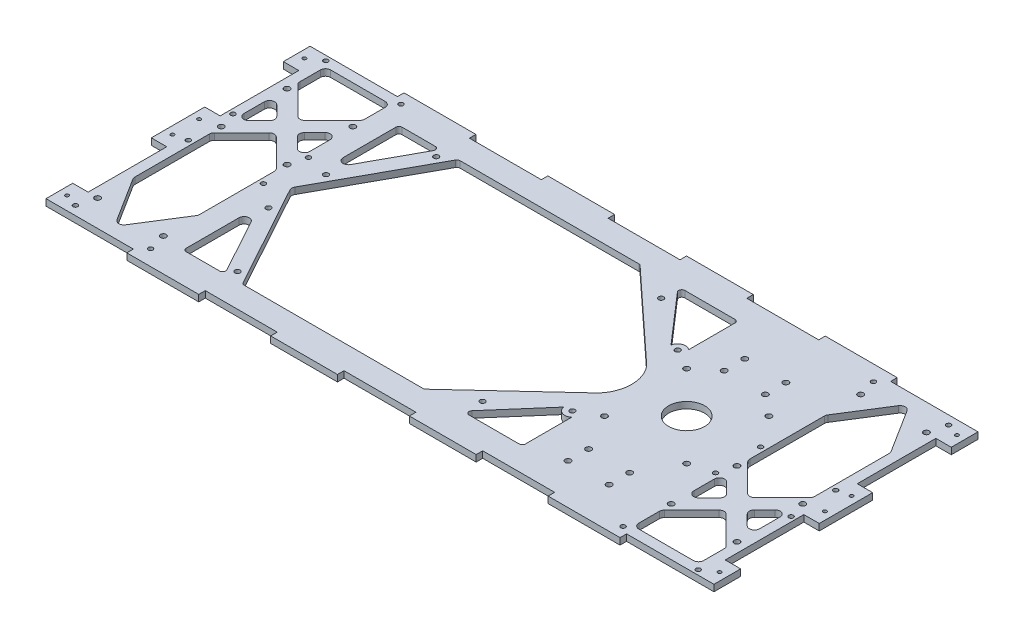
SolidWorks part; units mm, degrees
other "Markup1"
sketch "Sketch10" plane through (-309.99, 6.35, 134.85) normal (-0.3172, 0.7749, 0.5467) x (0.8454, -0.0301, 0.5333)
material "6061-T6 (SS)"
ref_plane "Alzado" through (0, 0, 0) normal (0, 0, 1) x (1, 0, 0)
ref_plane "Planta" through (0, 0, 0) normal (0, 1, 0) x (1, 0, 0)
ref_plane "Vista lateral" through (0, 0, 0) normal (1, 0, 0) x (0, 0, -1)
sketch "Sketch1" plane through (0, 0, 0) normal (0, 1, 0) x (1, 0, 0)
  line L1 (-309.99, -134.85) -> (309.99, -134.85)
  line L2 (-309.99, -134.85) -> (-309.99, 134.85)
  line L3 (-309.99, 134.85) -> (309.99, 134.85)
  line L4 (309.99, -134.85) -> (309.99, 134.85)
  line L5 (-309.99, -134.85) -> (309.99, 134.85) construction
  line L6 (-309.99, 134.85) -> (309.99, -134.85) construction
  point P0 (0, 0)
  dimension "D1" = 619.98
  dimension "D2" = 269.7
extrude "Boss-Extrude1" add sketch "Sketch1" along normal blind 6.35
sketch "Sketch3" plane through (0, 6.35, 0) normal (0, 1, 0) x (1, 0, 0)
  line L0 (309.99, 134.85) -> (-309.99, 134.85) construction
  line L1 (-300.44, 81.52) -> (-236.44, 81.52) construction
  line L2 (-300.44, 81.52) -> (-300.44, 17.52) construction
  line L3 (-300.44, 17.52) -> (-236.44, 17.52) construction
  line L4 (-236.44, 81.52) -> (-236.44, 17.52) construction
  line L5 (-300.44, 81.52) -> (-236.44, 17.52) construction
  line L6 (-300.44, 17.52) -> (-236.44, 81.52) construction
  line L7 (-309.99, 134.85) -> (-309.99, -134.85) construction
  line L8 (-309.99, -134.85) -> (309.99, -134.85) construction
  line L9 (300.44, -81.52) -> (236.44, -81.52) construction
  line L10 (300.44, -81.52) -> (300.44, -17.52) construction
  line L11 (300.44, -17.52) -> (236.44, -17.52) construction
  line L12 (236.44, -81.52) -> (236.44, -17.52) construction
  line L13 (300.44, -81.52) -> (236.44, -17.52) construction
  line L14 (300.44, -17.52) -> (236.44, -81.52) construction
  circle A0 centre (-300.44, -102.85) radius 2.75
  circle A1 centre (-236.44, -102.85) radius 2.75
  circle A2 centre (-300.44, 17.52) radius 2.75
  circle A3 centre (-236.44, 17.52) radius 2.75
  circle A4 centre (-236.44, 81.52) radius 2.75
  circle A5 centre (-300.44, 81.52) radius 2.75
  circle A6 centre (300.44, 102.85) radius 2.75
  circle A7 centre (236.44, 102.85) radius 2.75
  circle A8 centre (300.44, -17.52) radius 2.75
  circle A9 centre (236.44, -17.52) radius 2.75
  circle A10 centre (236.44, -81.52) radius 2.75
  circle A11 centre (300.44, -81.52) radius 2.75
  point P4 (-268.44, 49.52)
  point P25 (268.44, -49.52)
  point P34 (0, 0)
  dimension "D4" = 5.5
  dimension "D1" = 64
  dimension "D2" = 53.33
  dimension "D3" = 9.55
  dimension "D5" = 32
  dimension "D6" = 2
extrude "Cut-Extrude1" cut sketch "Sketch3" against normal blind 6.35
sketch "Sketch2" plane through (0, 6.35, 0) normal (0, 1, 0) x (1, 0, 0)
  line L0 (-309.99, -128.49) -> (309.99, -128.49)
  line L1 (-309.99, 134.85) -> (-309.99, -134.85) construction
  line L2 (309.99, -134.85) -> (309.99, 134.85) construction
  line L3 (-309.99, -134.85) -> (309.99, -134.85) construction
  line L4 (-309.99, 0) -> (309.99, 0) construction
  line L5 (-309.99, 128.49) -> (309.99, 128.49)
  line L6 (-309.99, 118.49) -> (309.99, 118.49)
  line L7 (-309.99, -118.49) -> (309.99, -118.49)
  circle A0 centre (0, 0) radius 5
  point P12 (0, 0)
  dimension "D2" = 10
  dimension "D1" = 6.36
  dimension "D3" = 10
sketch "Sketch6" plane through (0, 6.35, 0) normal (0, 1, 0) x (1, 0, 0)
  line L1 (-299.2185, -69.7126) -> (-272.6685, -111.7887)
  line L2 (-309.99, -118.49) -> (309.99, -118.49) construction
  line L5 (-300.44, 59.4489) -> (-300.44, 39.5911)
  line L6 (-300.44, 81.52) -> (-300.44, 17.52) construction
  line L7 (-291.9045, 36.0555) -> (-281.9755, 45.9845)
  line L8 (-281.9755, 53.0555) -> (-291.9045, 62.9845)
  line L9 (-268.44, 17.52) -> (-268.44, 81.52) construction
  line L10 (-300.44, 17.52) -> (-236.44, 17.52) construction
  line L11 (-254.9045, 53.0555) -> (-244.9755, 62.9845)
  line L12 (-244.9755, 36.0555) -> (-254.9045, 45.9845)
  line L13 (-236.44, 59.4489) -> (-236.44, 39.5911)
  line L14 (-299.99, 113.49) -> (-299.99, 93.5911)
  line L15 (-309.99, 118.49) -> (309.99, 118.49) construction
  line L16 (-298.5255, 90.0555) -> (-271.9755, 63.5055)
  line L17 (-264.9045, 63.5055) -> (-238.3545, 90.0555)
  line L18 (-236.89, 93.5911) -> (-236.89, 113.49)
  line L19 (-241.89, 118.49) -> (-294.99, 118.49)
  line L20 (-309.99, 134.85) -> (-309.99, -134.85) construction
  line L21 (-300.44, 81.52) -> (-236.44, 81.52) construction
  line L24 (-299.99, 5.4489) -> (-299.99, -67.0444)
  line L27 (-236.89, -67.0444) -> (-236.89, 5.4489)
  line L28 (-264.2115, -111.7887) -> (-237.6615, -69.7126)
  line L29 (299.2185, 69.7126) -> (272.6685, 111.7887)
  line L30 (-298.5255, 8.9845) -> (-271.9755, 35.5345)
  line L31 (-264.9045, 35.5345) -> (-238.3545, 8.9845)
  line L32 (300.44, -59.4489) -> (300.44, -39.5911)
  line L33 (291.9045, -36.0555) -> (281.9755, -45.9845)
  line L34 (281.9755, -53.0555) -> (291.9045, -62.9845)
  line L35 (254.9045, -53.0555) -> (244.9755, -62.9845)
  line L36 (244.9755, -36.0555) -> (254.9045, -45.9845)
  line L37 (236.44, -59.4489) -> (236.44, -39.5911)
  line L38 (299.99, -113.49) -> (299.99, -93.5911)
  line L39 (298.5255, -90.0555) -> (271.9755, -63.5055)
  line L40 (264.9045, -63.5055) -> (238.3545, -90.0555)
  line L41 (236.89, -93.5911) -> (236.89, -113.49)
  line L42 (241.89, -118.49) -> (294.99, -118.49)
  line L43 (299.99, -5.4489) -> (299.99, 67.0444)
  line L44 (236.89, 67.0444) -> (236.89, -5.4489)
  line L45 (264.2115, 111.7887) -> (237.6615, 69.7126)
  line L46 (298.5255, -8.9845) -> (271.9755, -35.5345)
  line L47 (264.9045, -35.5345) -> (238.3545, -8.9845)
  line L48 (268.44, -17.52) -> (268.44, -81.52) construction
  arc A0 (-238.3545, 90.0555) -> (-236.89, 93.5911) centre (-241.89, 93.5911) ccw
  arc A1 (-299.99, 93.5911) -> (-298.5255, 90.0555) centre (-294.99, 93.5911) ccw
  arc A2 (-271.9755, 63.5055) -> (-264.9045, 63.5055) centre (-268.44, 67.0411) ccw
  arc A3 (-300.44, 39.5911) -> (-291.9045, 36.0555) centre (-295.44, 39.5911) ccw
  arc A4 (-291.9045, 62.9845) -> (-300.44, 59.4489) centre (-295.44, 59.4489) ccw
  arc A5 (-281.9755, 45.9845) -> (-281.9755, 53.0555) centre (-285.5111, 49.52) ccw
  arc A6 (-254.9045, 53.0555) -> (-254.9045, 45.9845) centre (-251.3689, 49.52) ccw
  arc A7 (-244.9755, 36.0555) -> (-236.44, 39.5911) centre (-241.44, 39.5911) ccw
  arc A8 (-244.9755, 62.9845) -> (-236.44, 59.4489) centre (-241.44, 59.4489) cw
  arc A9 (-236.89, 113.49) -> (-241.89, 118.49) centre (-241.89, 113.49) ccw
  arc A10 (-299.99, 113.49) -> (-294.99, 118.49) centre (-294.99, 113.49) cw
  arc A11 (-272.6685, -111.7887) -> (-264.2115, -111.7887) centre (-268.44, -109.1204) ccw
  arc A12 (-237.6615, -69.7126) -> (-236.89, -67.0444) centre (-241.89, -67.0444) ccw
  arc A13 (-299.99, -67.0444) -> (-299.2185, -69.7126) centre (-294.99, -67.0444) ccw
  arc A14 (-238.3545, 8.9845) -> (-236.89, 5.4489) centre (-241.89, 5.4489) cw
  arc A15 (-298.5255, 8.9845) -> (-299.99, 5.4489) centre (-294.99, 5.4489) ccw
  arc A16 (-271.9755, 35.5345) -> (-264.9045, 35.5345) centre (-268.44, 31.9989) cw
  arc A17 (238.3545, -90.0555) -> (236.89, -93.5911) centre (241.89, -93.5911) ccw
  arc A18 (299.99, -93.5911) -> (298.5255, -90.0555) centre (294.99, -93.5911) ccw
  arc A19 (271.9755, -63.5055) -> (264.9045, -63.5055) centre (268.44, -67.0411) ccw
  arc A20 (300.44, -39.5911) -> (291.9045, -36.0555) centre (295.44, -39.5911) ccw
  arc A21 (291.9045, -62.9845) -> (300.44, -59.4489) centre (295.44, -59.4489) ccw
  arc A22 (281.9755, -45.9845) -> (281.9755, -53.0555) centre (285.5111, -49.52) ccw
  arc A23 (254.9045, -53.0555) -> (254.9045, -45.9845) centre (251.3689, -49.52) ccw
  arc A24 (244.9755, -36.0555) -> (236.44, -39.5911) centre (241.44, -39.5911) ccw
  arc A25 (244.9755, -62.9845) -> (236.44, -59.4489) centre (241.44, -59.4489) cw
  arc A26 (236.89, -113.49) -> (241.89, -118.49) centre (241.89, -113.49) ccw
  arc A27 (299.99, -113.49) -> (294.99, -118.49) centre (294.99, -113.49) cw
  arc A28 (272.6685, 111.7887) -> (264.2115, 111.7887) centre (268.44, 109.1204) ccw
  arc A29 (237.6615, 69.7126) -> (236.89, 67.0444) centre (241.89, 67.0444) ccw
  arc A30 (299.99, 67.0444) -> (299.2185, 69.7126) centre (294.99, 67.0444) ccw
  arc A31 (238.3545, -8.9845) -> (236.89, -5.4489) centre (241.89, -5.4489) cw
  arc A32 (298.5255, -8.9845) -> (299.99, -5.4489) centre (294.99, -5.4489) ccw
  arc A33 (271.9755, -35.5345) -> (264.9045, -35.5345) centre (268.44, -31.9989) cw
  point P37 (-299.99, 91.52)
  point P40 (-268.44, 59.97)
  point P43 (-300.44, 27.52)
  point P46 (-300.44, 71.52)
  point P49 (-278.44, 49.52)
  point P52 (-258.44, 49.52)
  point P55 (-236.44, 27.52)
  point P58 (-236.44, 71.52)
  point P61 (-236.89, 118.49)
  point P64 (-299.99, 118.49)
  point P67 (-268.44, -118.49)
  point P75 (-299.99, -68.49)
  point P78 (-236.89, 7.52)
  point P81 (-299.99, 7.52)
  point P84 (-268.44, 39.07)
  point P137 (0, 0)
  dimension "D5" = 5
  dimension "D8" = 5
  dimension "D1" = 10
  dimension "D2" = 10
  dimension "D3" = 10
  dimension "D4" = 20
  dimension "D6" = 50
  dimension "D7" = 20
  dimension "D9" = 2
extrude "Cut-Extrude2" cut sketch "Sketch6" against normal blind 6.35
sketch "Sketch7" plane through (0, 6.35, 0) normal (0, 1, 0) x (1, 0, 0)
  line L0 (-309.99, 0) -> (309.99, 0) construction
  line L1 (309.99, -134.85) -> (309.99, 134.85) construction
  line L2 (209.99, -40) -> (129.99, -40) construction
  line L3 (209.99, -40) -> (209.99, 40) construction
  line L4 (209.99, 40) -> (129.99, 40) construction
  line L5 (129.99, -40) -> (129.99, 40) construction
  line L6 (209.99, -40) -> (129.99, 40) construction
  line L7 (209.99, 40) -> (129.99, -40) construction
  line L8 (129.99, 0) -> (209.99, 0) construction
  line L9 (149.99, -95.5) -> (189.99, -75.5) construction
  line L10 (149.99, -75.5) -> (189.99, -95.5) construction
  line L11 (149.99, 56.5) -> (189.99, 56.5) construction
  line L12 (149.99, 56.5) -> (149.99, 76.5) construction
  line L13 (149.99, 76.5) -> (189.99, 76.5) construction
  line L14 (189.99, 56.5) -> (189.99, 76.5) construction
  line L15 (149.99, 56.5) -> (189.99, 76.5) construction
  line L16 (149.99, 76.5) -> (189.99, 56.5) construction
  line L17 (189.99, -75.5) -> (189.99, -95.5) construction
  line L18 (149.99, -95.5) -> (189.99, -95.5) construction
  line L19 (149.99, -75.5) -> (149.99, -95.5) construction
  line L20 (149.99, -75.5) -> (189.99, -75.5) construction
  circle A0 centre (169.99, 0) radius 17.5
  circle A1 centre (129.99, 40) radius 2.75
  circle A2 centre (209.99, 40) radius 2.75
  circle A3 centre (209.99, -40) radius 2.75
  circle A4 centre (129.99, -40) radius 2.75
  circle A5 centre (149.99, 76.5) radius 2.75
  circle A6 centre (189.99, 76.5) radius 2.75
  circle A7 centre (189.99, 56.5) radius 2.75
  circle A8 centre (149.99, 56.5) radius 2.75
  circle A9 centre (149.99, -75.5) radius 2.75
  circle A10 centre (189.99, -75.5) radius 2.75
  circle A11 centre (189.99, -95.5) radius 2.75
  circle A12 centre (149.99, -95.5) radius 2.75
  point P10 (169.99, 66.5)
  point P20 (169.99, 0)
  point P37 (169.99, -85.5)
  dimension "D1" = 40
  dimension "D2" = 5.5
  dimension "D5" = 35
  dimension "D6" = 4
  dimension "D10" = 95.5
  dimension "D8" = 76.5
  dimension "D3" = 80
  dimension "D4" = 140
  dimension "D7" = 20
  dimension "D9" = 40
extrude "Cut-Extrude3" cut sketch "Sketch7" against normal blind 6.35
sketch "Sketch8" plane through (0, 6.35, 0) normal (0, 1, 0) x (1, 0, 0)
  line L0 (104.0255, 15) -> (30, 15)
  line L1 (3.6808, 2.4048) -> (-58.5763, 115.8948)
  line L2 (-151.4237, 115.8948) -> (-213.6808, 2.4048)
  line L3 (-147.0399, 118.49) -> (-62.9601, 118.49)
  line L4 (115, -51.2273) -> (115, -113.49)
  line L5 (25, 20) -> (25, 105.1211)
  line L6 (52.0804, -110.2089) -> (106.2271, -47.9462)
  line L7 (-309.99, 118.49) -> (309.99, 118.49) construction
  line L8 (33.7729, 108.4022) -> (107.7984, 23.2811)
  line L9 (-309.99, 0) -> (309.99, 0) construction
  line L10 (0, -118.49) -> (0, 118.49) construction
  line L11 (-309.99, 0) -> (309.99, 0) construction
  line L12 (52.0804, 110.2089) -> (106.2271, 47.9462)
  line L13 (115, 51.2273) -> (115, 113.49)
  line L14 (110, 118.49) -> (55.8533, 118.49)
  line L15 (110, -118.49) -> (55.8533, -118.49)
  line L16 (25, -20) -> (25, -105.1211)
  line L17 (104.0255, -15) -> (30, -15)
  line L18 (33.7729, -108.4022) -> (107.7984, -23.2811)
  line L19 (-151.4237, -115.8948) -> (-213.6808, -2.4048)
  line L20 (-147.0399, -118.49) -> (-62.9601, -118.49)
  line L21 (3.6808, -2.4048) -> (-58.5763, -115.8948)
  line L22 (-34.4455, 118.49) -> (0, 118.49)
  line L23 (5, 113.49) -> (5, 50.6985)
  line L24 (-4.3837, 48.2937) -> (-38.8292, 111.0852)
  line L25 (-105, 118.49) -> (-105, -118.49) construction
  line L26 (-175.5545, 118.49) -> (-210, 118.49)
  line L27 (-205.6163, 48.2937) -> (-171.1708, 111.0852)
  line L28 (-215, 113.49) -> (-215, 50.6985)
  line L29 (-205.6163, -48.2937) -> (-171.1708, -111.0852)
  line L30 (-215, -113.49) -> (-215, -50.6985)
  line L31 (-175.5545, -118.49) -> (-210, -118.49)
  line L32 (5, -113.49) -> (5, -50.6985)
  line L33 (-34.4455, -118.49) -> (0, -118.49)
  line L34 (-4.3837, -48.2937) -> (-38.8292, -111.0852)
  arc A0 (-215, -113.49) -> (-210, -118.49) centre (-210, -113.49) ccw
  arc A1 (-171.1708, -111.0852) -> (-175.5545, -118.49) centre (-175.5545, -113.49) cw
  arc A2 (-205.6163, -48.2937) -> (-215, -50.6985) centre (-210, -50.6985) ccw
  arc A3 (-151.4237, -115.8948) -> (-147.0399, -118.49) centre (-147.0399, -113.49) ccw
  arc A4 (-62.9601, -118.49) -> (-58.5763, -115.8948) centre (-62.9601, -113.49) ccw
  arc A5 (-34.4455, -118.49) -> (-38.8292, -111.0852) centre (-34.4455, -113.49) cw
  arc A6 (5, -113.49) -> (0, -118.49) centre (0, -113.49) cw
  arc A7 (5, -50.6985) -> (-4.3837, -48.2937) centre (0, -50.6985) ccw
  arc A8 (25, -20) -> (30, -15) centre (30, -20) cw
  arc A9 (25, -105.1211) -> (33.7729, -108.4022) centre (30, -105.1211) ccw
  arc A10 (52.0804, -110.2089) -> (55.8533, -118.49) centre (55.8533, -113.49) ccw
  arc A11 (115, -113.49) -> (110, -118.49) centre (110, -113.49) cw
  arc A12 (104.0255, -15) -> (107.7984, -23.2811) centre (104.0255, -20) cw
  arc A13 (115, -51.2273) -> (106.2271, -47.9462) centre (110, -51.2273) ccw
  arc A14 (115, 113.49) -> (110, 118.49) centre (110, 113.49) ccw
  arc A15 (52.0804, 110.2089) -> (55.8533, 118.49) centre (55.8533, 113.49) cw
  arc A16 (106.2271, 47.9462) -> (115, 51.2273) centre (110, 51.2273) ccw
  arc A17 (104.0255, 15) -> (107.7984, 23.2811) centre (104.0255, 20) ccw
  arc A18 (25, 105.1211) -> (33.7729, 108.4022) centre (30, 105.1211) cw
  arc A19 (30, 15) -> (25, 20) centre (30, 20) cw
  arc A20 (5, 50.6985) -> (-4.3837, 48.2937) centre (0, 50.6985) cw
  arc A21 (0, 118.49) -> (5, 113.49) centre (0, 113.49) cw
  arc A22 (-34.4455, 118.49) -> (-38.8292, 111.0852) centre (-34.4455, 113.49) ccw
  arc A23 (-151.4237, 115.8948) -> (-147.0399, 118.49) centre (-147.0399, 113.49) cw
  arc A24 (-58.5763, 115.8948) -> (-62.9601, 118.49) centre (-62.9601, 113.49) ccw
  arc A25 (3.6808, 2.4048) -> (3.6808, -2.4048) centre (-0.7029, 0) cw
  arc A26 (-213.6808, 2.4048) -> (-213.6808, -2.4048) centre (-209.2971, 0) ccw
  arc A27 (-205.6163, 48.2937) -> (-215, 50.6985) centre (-210, 50.6985) cw
  arc A28 (-175.5545, 118.49) -> (-171.1708, 111.0852) centre (-175.5545, 113.49) cw
  arc A29 (-210, 118.49) -> (-215, 113.49) centre (-210, 113.49) ccw
  point P12 (0, 0)
  point P16 (0, 0)
  point P46 (-215, -118.49)
  point P49 (-167.1087, -118.49)
  point P52 (-215, -31.1879)
  point P55 (-150, -118.49)
  point P58 (-60, -118.49)
  point P61 (-42.8913, -118.49)
  point P64 (5, -118.49)
  point P67 (5, -31.1879)
  point P70 (25, -15)
  point P73 (25, -118.49)
  point P76 (44.8788, -118.49)
  point P79 (115, -118.49)
  point P82 (115, -15)
  point P85 (115, -37.8584)
  point P88 (115, 118.49)
  point P91 (44.8788, 118.49)
  point P94 (115, 37.8584)
  point P97 (115, 15)
  point P100 (25, 118.49)
  point P103 (25, 15)
  point P106 (5, 31.1879)
  point P109 (5, 118.49)
  point P112 (-42.8913, 118.49)
  point P115 (-150, 118.49)
  point P118 (-60, 118.49)
  point P121 (5, 0)
  point P124 (-215, 0)
  point P127 (-215, 31.1879)
  point P130 (-167.1087, 118.49)
  point P133 (-215, 118.49)
  dimension "D10" = 5
  dimension "D1" = 15
  dimension "D2" = 90
  dimension "D3" = 50
  dimension "D4" = 15
  dimension "D5" = 90
  dimension "D6" = 20
  dimension "D7" = 60
  dimension "D8" = 20
  dimension "D9" = 15
extrude "Cut-Extrude4" cut sketch "Sketch8" against normal blind 6.35
sketch "Sketch9" plane through (0, 6.35, 0) normal (0, 1, 0) x (1, 0, 0)
  line L0 (-309.99, -134.85) -> (309.99, -134.85) construction
  line L1 (-309.99, -128.49) -> (-239.99, -128.49)
  line L2 (-309.99, -128.49) -> (-309.99, -134.85)
  line L3 (-309.99, -134.85) -> (-239.99, -134.85)
  line L4 (-239.99, -128.49) -> (-239.99, -134.85)
  line L5 (-309.99, -128.49) -> (-239.99, -134.85) construction
  line L6 (-309.99, -134.85) -> (-239.99, -128.49) construction
  line L7 (-309.99, -128.49) -> (309.99, -128.49) construction
  line L8 (-169.99, -128.49) -> (-99.99, -128.49)
  line L9 (-169.99, -128.49) -> (-169.99, -134.85)
  line L10 (-169.99, -134.85) -> (-99.99, -134.85)
  line L11 (-99.99, -128.49) -> (-99.99, -134.85)
  line L12 (-169.99, -128.49) -> (-99.99, -134.85) construction
  line L13 (-169.99, -134.85) -> (-99.99, -128.49) construction
  line L14 (0, 0) -> (0, -134.85) construction
  line L16 (-35, -128.49) -> (35, -128.49)
  line L17 (-35, -128.49) -> (-35, -134.85)
  line L18 (-35, -134.85) -> (35, -134.85)
  line L19 (35, -128.49) -> (35, -134.85)
  line L20 (-35, -128.49) -> (35, -134.85) construction
  line L21 (-35, -134.85) -> (35, -128.49) construction
  line L22 (309.99, -134.85) -> (239.99, -134.85)
  line L23 (309.99, -134.85) -> (309.99, -128.49)
  line L24 (309.99, -128.49) -> (239.99, -128.49)
  line L25 (239.99, -134.85) -> (239.99, -128.49)
  line L26 (309.99, -134.85) -> (239.99, -128.49) construction
  line L27 (309.99, -128.49) -> (239.99, -134.85) construction
  line L28 (169.99, -128.49) -> (99.99, -128.49)
  line L29 (169.99, -128.49) -> (169.99, -134.85)
  line L30 (169.99, -134.85) -> (99.99, -134.85)
  line L31 (99.99, -128.49) -> (99.99, -134.85)
  line L32 (169.99, -128.49) -> (99.99, -134.85) construction
  line L33 (169.99, -134.85) -> (99.99, -128.49) construction
  point P4 (-274.99, -131.67)
  point P12 (-134.99, -131.67)
  point P22 (0, -131.67)
  point P27 (274.99, -131.67)
  point P33 (134.99, -131.67)
  dimension "D1" = 70
  dimension "D2" = 70
  dimension "D3" = 70
  dimension "D4" = 70
  dimension "D5" = 64.99
  dimension "D6" = 70
  dimension "D7" = 70
  dimension "D8" = 70
  dimension "D9" = 64.99
extrude "Cut-Extrude5" cut sketch "Sketch9" against normal blind 6.35
mirror "Mirror1" about plane through (0, 0, 0) normal (0, 0, 1) of "Cut-Extrude5"
sketch "Sketch11" plane through (0, 6.35, 0) normal (0, 1, 0) x (1, 0, 0)
  line L0 (-70.6451, 118.49) -> (25, 118.49)
  line L1 (-62.9601, 118.49) -> (-147.0399, 118.49) construction
  line L2 (25, 118.49) -> (107.7984, 23.2811)
  line L3 (107.7984, -23.2811) -> (25, -118.49)
  line L4 (25, -118.49) -> (-70.6451, -118.49)
  line L5 (-147.0399, -118.49) -> (-62.9601, -118.49) construction
  line L6 (107.7984, 23.2811) -> (33.7729, 108.4022) construction
  line L7 (-34.4455, -118.49) -> (0, -118.49) construction
  line L8 (-70.6451, -118.49) -> (-70.6451, 118.49)
  arc A0 (107.7984, 23.2811) -> (107.7984, -23.2811) centre (81.0277, 0) cw
extrude "Cut-Extrude6" cut sketch "Sketch11" against normal blind 10
sketch "Sketch12" plane through (0, 6.35, 0) normal (0, 1, 0) x (1, 0, 0)
  line L0 (5, -118.49) -> (107.7984, -23.2811)
  line L1 (-147.0399, -118.49) -> (25, -118.49) construction
  line L2 (107.7984, -23.2811) -> (25, -118.49)
  line L3 (25, -118.49) -> (5, -118.49)
  line L4 (0, 0) -> (309.99, 0) construction
  line L5 (309.99, -128.49) -> (309.99, 128.49) construction
  line L6 (107.7984, 23.2811) -> (25, 118.49)
  line L7 (5, 118.49) -> (107.7984, 23.2811)
  line L8 (25, 118.49) -> (5, 118.49)
  dimension "D1" = 20
extrude "Boss-Extrude2" add sketch "Sketch12" against normal up to surface (6.35 mm away) up to face at (-75.1312, 0, 0)
sketch "Sketch13" plane through (0, 6.35, 0) normal (0, 1, 0) x (1, 0, 0)
  line L0 (-169.99, 134.85) -> (-239.99, 134.85) construction
  line L1 (-218, 134.85) -> (118, 134.85)
  line L2 (-218, 134.85) -> (-218, -134.85)
  line L3 (-218, -134.85) -> (118, -134.85)
  line L4 (118, 134.85) -> (118, -134.85)
  line L5 (-218, 134.85) -> (118, -134.85) construction
  line L6 (-218, -134.85) -> (118, 134.85) construction
  line L8 (-50, 134.85) -> (-50, -134.85)
  line L9 (115, 51.2273) -> (115, 113.49) construction
  line L10 (-215, -50.6985) -> (-215, -113.49) construction
  line L11 (35, -134.85) -> (99.99, -134.85) construction
  point P4 (-50, 0)
  dimension "D1" = 3
  dimension "D2" = 3
  dimension "D3" = 168
sketch "Sketch14" plane through (0, 6.35, 0) normal (0, 1, 0) x (1, 0, 0)
  circle A0 centre (110, 51.2273) radius 7.5
  circle A2 centre (110, 51.2273) radius 2.5
  circle A3 centre (110, -51.2273) radius 7.5
  circle A4 centre (110, -51.2273) radius 2.5
  dimension "D1" = 5
  dimension "D2" = 15
  dimension "D3" = 15
  dimension "D4" = 5
extrude "Boss-Extrude3" add sketch "Sketch14" against normal up to surface (6.35 mm away) up to face at (-79.1312, 0, 0)
sketch "Sketch15" plane through (0, 6.35, 0) normal (0, 1, 0) x (1, 0, 0)
  line L0 (0, 0) -> (-309.99, 0) construction
  line L1 (-309.99, -128.49) -> (-324.99, -128.49)
  line L2 (-309.99, -128.49) -> (-309.99, -102.49)
  line L3 (-309.99, -102.49) -> (-324.99, -102.49)
  line L4 (-324.99, -128.49) -> (-324.99, -102.49)
  line L5 (-309.99, -128.49) -> (-324.99, -102.49) construction
  line L6 (-309.99, -102.49) -> (-324.99, -128.49) construction
  line L7 (-309.99, 128.49) -> (-309.99, -128.49) construction
  line L9 (-309.99, 26) -> (-324.99, 26)
  line L10 (-309.99, 26) -> (-309.99, -26)
  line L11 (-309.99, -26) -> (-324.99, -26)
  line L12 (-324.99, 26) -> (-324.99, -26)
  line L13 (-309.99, 26) -> (-324.99, -26) construction
  line L14 (-309.99, -26) -> (-324.99, 26) construction
  line L15 (-309.99, 128.49) -> (-324.99, 128.49)
  line L16 (-309.99, 128.49) -> (-309.99, 102.49)
  line L17 (-309.99, 102.49) -> (-324.99, 102.49)
  line L18 (-324.99, 128.49) -> (-324.99, 102.49)
  line L19 (-309.99, 128.49) -> (-324.99, 102.49) construction
  line L20 (-309.99, 102.49) -> (-324.99, 128.49) construction
  point P4 (-317.49, -115.49)
  point P15 (-317.49, 0)
  point P21 (-317.49, 115.49)
  dimension "D1" = 15
  dimension "D2" = 26
  dimension "D3" = 52
  dimension "D4" = 26
extrude "Boss-Extrude4" add sketch "Sketch15" against normal up to surface (6.35 mm away) contours L12 L11 L10 L9 | L4 L3 L2 L1 | L18 L17 L16 L15 up to face at (91.243, 0, 95.9452)
sketch "Sketch16" plane through (0, 6.35, 0) normal (0, 1, 0) x (1, 0, 0)
  line L0 (-309.99, -128.49) -> (-324.99, -102.49) construction
  line L1 (-324.99, 26) -> (-309.99, 26) construction
  line L2 (-324.99, 26) -> (-324.99, 0) construction
  line L3 (-324.99, 0) -> (-309.99, 0) construction
  line L4 (-309.99, 26) -> (-309.99, 0) construction
  line L5 (-324.99, 26) -> (-309.99, 0) construction
  line L6 (-324.99, 0) -> (-309.99, 26) construction
  line L7 (-324.99, -26) -> (-309.99, -26) construction
  line L8 (-324.99, -26) -> (-324.99, 0) construction
  line L9 (-324.99, 0) -> (-309.99, 0) construction
  line L10 (-309.99, -26) -> (-309.99, 0) construction
  line L11 (-324.99, -26) -> (-309.99, 0) construction
  line L12 (-324.99, 0) -> (-309.99, -26) construction
  circle A0 centre (-317.49, 115.49) radius 1.75
  circle A1 centre (-317.49, 13) radius 1.75
  circle A2 centre (-317.49, -13) radius 1.75
  circle A3 centre (-317.49, -115.49) radius 1.75
  point P7 (-317.49, 13)
  point P16 (-317.49, -13)
  dimension "D1" = 3.5
extrude "Cut-Extrude7" cut sketch "Sketch16" against normal blind 25
mirror "Mirror2" about plane through (0, 0, 0) normal (1, 0, 0) of "Boss-Extrude4", "Cut-Extrude7"
sketch "Sketch18" plane through (0, 6.35, 0) normal (0, 1, 0) x (1, 0, 0)
  line L0 (-218, 134.85) -> (118, -134.85) construction
  line L1 (-218, -134.85) -> (118, 134.85) construction
  line L2 (0, 0) -> (-218, 0) construction
  line L4 (-209, -28) -> (-209, 28) construction
  line L5 (-218, 134.85) -> (-218, -134.85) construction
  line L8 (-151.4237, 115.8948) -> (-213.6808, 2.4048) construction
  line L9 (-213.6808, -2.4048) -> (-151.4237, -115.8948) construction
  line L10 (107.7984, -23.2811) -> (5, -118.49) construction
  line L11 (5, 118.49) -> (107.7984, 23.2811) construction
  circle A0 centre (-170.4967, 96.7201) radius 2.5
  circle A1 centre (-170.4967, -96.7201) radius 2.5
  circle A2 centre (58.2503, -86.8902) radius 2.5
  circle A3 centre (58.2503, 86.8902) radius 2.5
  circle A4 centre (-209, 28) radius 2.5
  circle A5 centre (-209, -28) radius 2.5
  point P24 (-209, 0)
  dimension "D1" = 9
  dimension "D2" = 5
  dimension "D3" = 56
  dimension "D4" = 7.5
  dimension "D5" = 7.5
  dimension "D6" = 13
  dimension "D7" = 13
extrude "Cut-Extrude8" cut sketch "Sketch18" against normal blind 25
sketch "Sketch19" plane through (0, 6.35, 0) normal (0, 1, 0) x (1, 0, 0)
  line L0 (0, -105) -> (0, 105) construction
  line L1 (-215, -105) -> (115, -105)
  line L2 (-215, -50.6985) -> (-215, -113.49) construction
  line L3 (115, -113.49) -> (115, -56.8174) construction
  line L4 (115, -105) -> (115, -121)
  line L5 (115, -121) -> (-215, -121)
  line L6 (-215, -121) -> (-215, -105)
  line L7 (-215, 105) -> (-215, 121)
  line L8 (-215, 113.49) -> (-215, 50.6985) construction
  line L9 (-215, 121) -> (115, 121)
  line L10 (115, 121) -> (115, 105)
  line L11 (115, 56.8174) -> (115, 113.49) construction
  line L12 (115, 105) -> (-215, 105)
  point P4 (0, 0)
  dimension "D1" = 210
  dimension "D2" = 16
  dimension "D3" = 16
extrude "Boss-Extrude5" add sketch "Sketch19" against normal up to surface (6.35 mm away) up to face at (-170.4967, 0, -99.2201)
fillet "Fillet1" radius 3 12 edges at (-174.5089, 3.175, 105) (-157.4002, 3.175, 105) (-215, 3.175, 105) (19.5653, 3.175, 105) (56.6103, 3.175, 105) (115, 3.175, 105) (115, 3.175, -105) (56.6103, 3.175, -105) (19.5653, 3.175, -105) (-157.4002, 3.175, -105) (-174.5089, 3.175, -105) (-215, 3.175, -105)
sketch "Sketch20" plane through (0, 0, 0) normal (0, -1, 0) x (-1, 0, 0)
  circle A0 centre (-304.99, 119.85) radius 2.25
  circle A1 centre (-231.89, 119.85) radius 2.25
  circle A2 centre (-304.99, 10) radius 2.25
  circle A3 centre (-231.89, 10) radius 2.25
  circle A4 centre (-305.44, -33.85) radius 2.25
  circle A5 centre (-231.89, -33.85) radius 2.25
  circle A6 centre (-304.99, -123.85) radius 2.25
  circle A7 centre (-232.0222, -123.9657) radius 2.25
  circle A8 centre (231.89, -119.85) radius 2.25
  circle A9 centre (304.99, -119.85) radius 2.25
  circle A10 centre (304.99, -10) radius 2.25
  circle A11 centre (231.89, -10) radius 2.25
  circle A12 centre (231.89, 33.85) radius 2.25
  circle A13 centre (305.44, 33.85) radius 2.25
  circle A14 centre (304.99, 123.85) radius 2.25
  circle A15 centre (231.89, 123.85) radius 2.25
  dimension "D1" = 4.5
extrude "Cut-Extrude9" cut sketch "Sketch20" against normal up to surface (6.35 mm away) up to face at (-62.8393, 6.35, 0)
